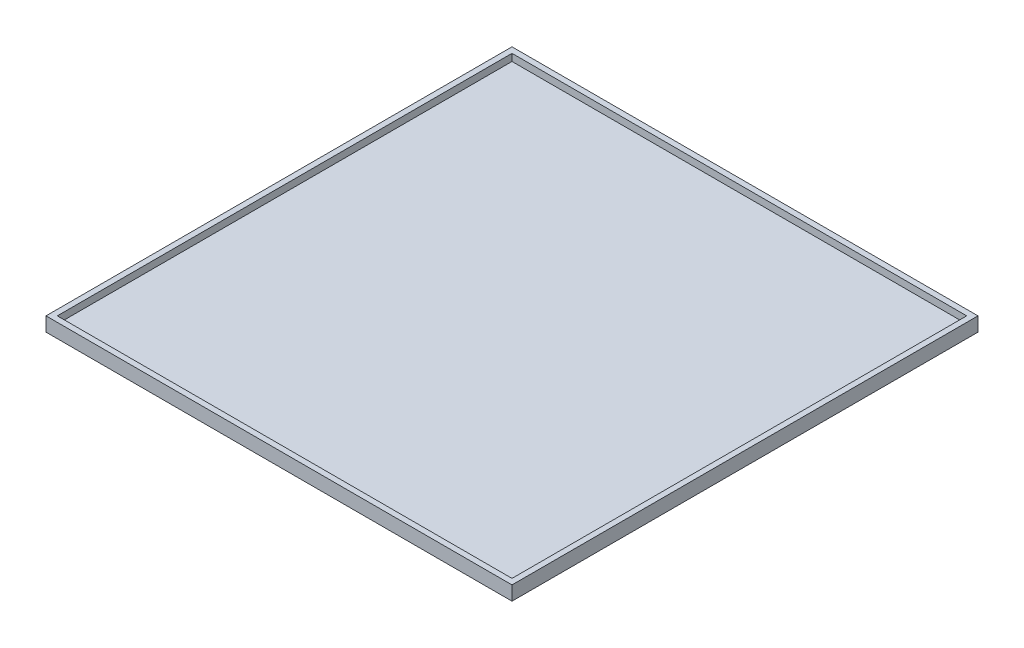
SolidWorks part; units mm, degrees
other "Markup1"
sketch "Sketch3" plane through (-103.1875, 6.35, 103.1875) normal (-0.6948, 0.7159, 0.0689) x (0.7166, 0.6811, 0.1502)
ref_plane "Front Plane" through (0, 0, 0) normal (0, 0, 1) x (1, 0, 0)
ref_plane "Top Plane" through (0, 0, 0) normal (0, 1, 0) x (1, 0, 0)
ref_plane "Right Plane" through (0, 0, 0) normal (1, 0, 0) x (0, 0, -1)
sketch "Sketch1" plane through (0, 0, 0) normal (0, 1, 0) x (1, 0, 0)
  line L1 (-104.775, -104.775) -> (104.775, -104.775)
  line L2 (-104.775, -104.775) -> (-104.775, 104.775)
  line L3 (-104.775, 104.775) -> (104.775, 104.775)
  line L4 (104.775, -104.775) -> (104.775, 104.775)
  line L5 (-104.775, -104.775) -> (104.775, 104.775) construction
  line L6 (-104.775, 104.775) -> (104.775, -104.775) construction
  point P0 (0, 0)
  dimension "D1" = 209.55
  dimension "D2" = 209.55
extrude "Boss-Extrude1" add sketch "Sketch1" along normal blind 6.35
sketch "Sketch2" plane through (0, 6.35, 0) normal (0, 1, 0) x (1, 0, 0)
  line L0 (-104.775, 104.775) -> (-104.775, -104.775) construction
  line L1 (-102.235, -102.235) -> (102.235, -102.235)
  line L2 (-102.235, -102.235) -> (-102.235, 102.235)
  line L3 (-102.235, 102.235) -> (102.235, 102.235)
  line L4 (102.235, -102.235) -> (102.235, 102.235)
  line L5 (-102.235, -102.235) -> (102.235, 102.235) construction
  line L6 (-102.235, 102.235) -> (102.235, -102.235) construction
  line L7 (104.775, 104.775) -> (-104.775, 104.775) construction
  point P0 (0, 0)
  dimension "D1" = 2.54
  dimension "D2" = 2.54
extrude "Cut-Extrude1" cut sketch "Sketch2" against normal blind 3.175
